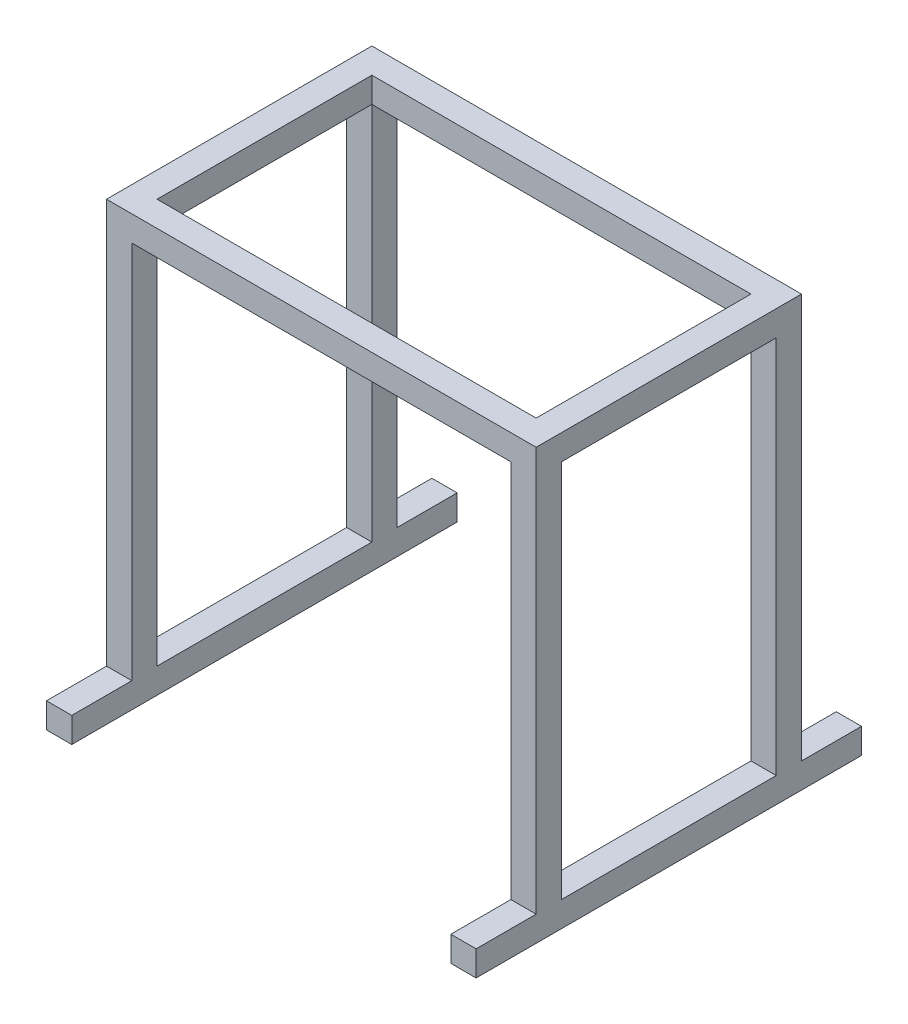
SolidWorks part; units mm, degrees
ref_plane "Front Plane" through (0, 0, 0) normal (0, 0, 1) x (1, 0, 0)
ref_plane "Top Plane" through (0, 0, 0) normal (0, 1, 0) x (1, 0, 0)
ref_plane "Right Plane" through (0, 0, 0) normal (1, 0, 0) x (0, 0, -1)
sketch "Sketch1" plane through (0, 0, 0) normal (0, 1, 0) x (1, 0, 0)
  line L1 (-170, -105) -> (170, -105)
  line L2 (-170, -105) -> (-170, 105)
  line L3 (-170, 105) -> (170, 105)
  line L4 (170, -105) -> (170, 105)
  line L5 (-170, -105) -> (170, 105) construction
  line L6 (-170, 105) -> (170, -105) construction
  point P0 (0, 0)
  dimension "D1" = 210
  dimension "D2" = 340
extrude "Boss-Extrude1" add sketch "Sketch1" against normal blind 320
sketch "Sketch2" plane through (0, 0, 0) normal (0, 1, 0) x (1, 0, 0)
  line L8 (150, -85) -> (150, 85)
  line L9 (150, 85) -> (-150, 85)
  line L10 (-150, 85) -> (-150, -85)
  line L11 (-150, -85) -> (150, -85)
  line L12 (150, -85) -> (150, 85)
  line L13 (150, 85) -> (-150, 85)
  line L14 (-150, 85) -> (-150, -85)
  line L15 (-150, -85) -> (150, -85)
  dimension "D1" = 20
extrude "Cut-Extrude1" cut sketch "Sketch2" against normal through all
sketch "Sketch3" plane through (0, 0, 105) normal (0, 0, 1) x (1, 0, 0)
  line L0 (-170, 0) -> (170, 0) construction
  line L1 (150, -620) -> (-150, -620)
  line L2 (150, -620) -> (150, -20)
  line L3 (150, -20) -> (-150, -20)
  line L4 (-150, -620) -> (-150, -20)
  line L5 (150, -620) -> (-150, -20) construction
  line L6 (150, -20) -> (-150, -620) construction
  line L7 (-170, -320) -> (-170, 0) construction
  line L8 (-170, -320) -> (170, -320) construction
  point P0 (0, -320)
  dimension "D1" = 20
  dimension "D2" = 20
extrude "Cut-Extrude2" cut sketch "Sketch3" against normal through all
sketch "Sketch4" plane through (170, 0, 0) normal (1, 0, 0) x (0, 0, -1)
  line L0 (-105, -320) -> (105, -320) construction
  line L1 (85, -620) -> (-85, -620)
  line L2 (85, -620) -> (85, -20)
  line L3 (85, -20) -> (-85, -20)
  line L4 (-85, -620) -> (-85, -20)
  line L5 (85, -620) -> (-85, -20) construction
  line L6 (85, -20) -> (-85, -620) construction
  line L7 (-85, -20) -> (-85, 0) construction
  point P0 (0, -320)
extrude "Cut-Extrude3" cut sketch "Sketch4" against normal through all
sketch "Sketch5" plane through (0, 0, 0) normal (0, 0, 1) x (1, 0, 0)
  line L1 (-170, -320) -> (-150, -320)
  line L2 (-170, -320) -> (-170, -340)
  line L3 (-170, -340) -> (-150, -340)
  line L4 (-150, -320) -> (-150, -340)
  line L5 (150, -320) -> (190, -320)
  line L6 (150, -320) -> (150, -340)
  line L7 (150, -340) -> (190, -340)
  line L8 (190, -320) -> (190, -340)
  dimension "D1" = 20
  dimension "D2" = 40
extrude "Boss-Extrude2" add sketch "Sketch5" along normal blind 152.5 and the other way blind 152.5
sketch "Sketch6" plane through (0, -320, 0) normal (0, 1, 0) x (1, 0, 0)
  line L0 (190, -152.5) -> (150, -152.5) construction
  line L1 (190, 152.5) -> (170, 152.5)
  line L2 (190, 152.5) -> (190, -152.5)
  line L3 (190, -152.5) -> (170, -152.5)
  line L4 (170, 152.5) -> (170, -152.5)
  line L5 (170, -105) -> (170, 105) construction
extrude "Cut-Extrude4" cut sketch "Sketch6" against normal through all
